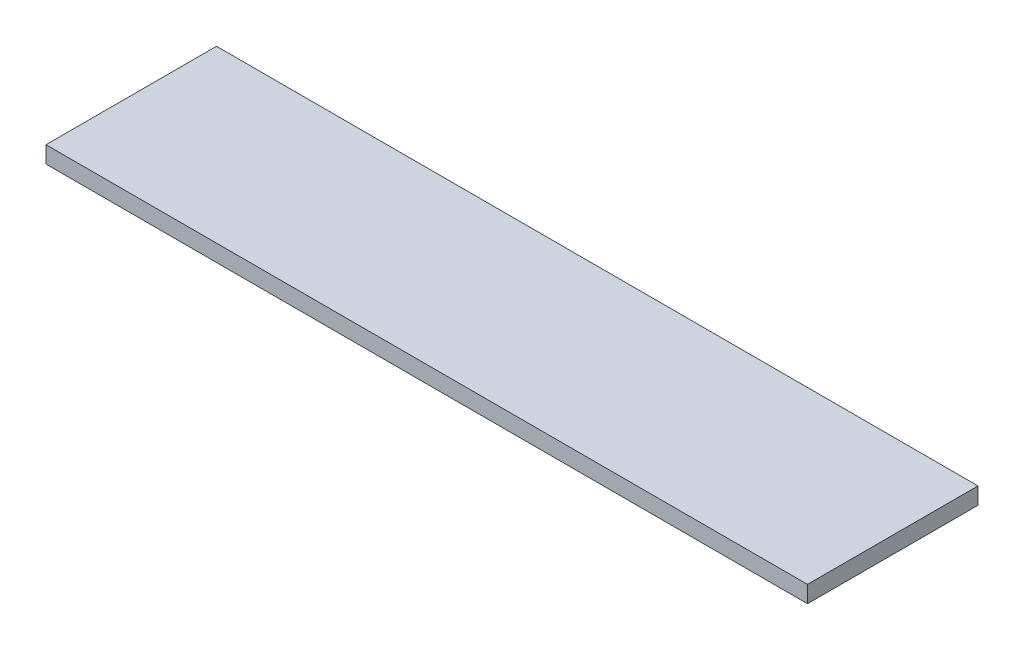
SolidWorks part; units mm, degrees
ref_plane "Front Plane" through (0, 0, 0) normal (0, 0, 1) x (1, 0, 0)
ref_plane "Top Plane" through (0, 0, 0) normal (0, 1, 0) x (1, 0, 0)
ref_plane "Right Plane" through (0, 0, 0) normal (1, 0, 0) x (0, 0, -1)
sketch "Sketch1" plane through (0, 0, 0) normal (0, 1, 0) x (1, 0, 0)
  line L1 (-45.375, 10.16) -> (45.375, 10.16)
  line L2 (-45.375, 10.16) -> (-45.375, -10.16)
  line L3 (-45.375, -10.16) -> (45.375, -10.16)
  line L4 (45.375, 10.16) -> (45.375, -10.16)
  line L5 (-45.375, 10.16) -> (45.375, -10.16) construction
  line L6 (-45.375, -10.16) -> (45.375, 10.16) construction
  point P0 (0, 0)
  dimension "D1" = 20.32
  dimension "D2" = 90.75
extrude "Boss-Extrude1" add sketch "Sketch1" along normal blind 2
